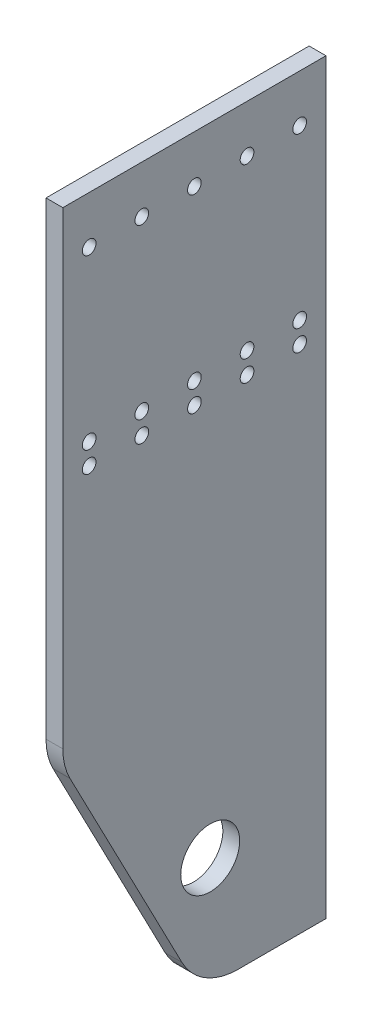
SolidWorks part; units mm, degrees
material "Q355"
ref_plane "前视基准面" through (0, 0, 0) normal (0, 0, 1) x (1, 0, 0)
ref_plane "上视基准面" through (0, 0, 0) normal (0, 1, 0) x (1, 0, 0)
ref_plane "右视基准面" through (0, 0, 0) normal (1, 0, 0) x (0, 0, -1)
sketch "草图1" plane through (0, 0, 0) normal (1, 0, 0) x (0, 0, -1)
  line L1 (0, 0) -> (250, 0)
  line L2 (0, 0) -> (0, 750)
  line L3 (0, 750) -> (250, 750)
  line L4 (250, 0) -> (250, 750)
  dimension "D1" = 250
  dimension "D2" = 750
extrude "凸台-拉伸1" add sketch "草图1" along normal blind 16 contours L2 L3 L4 L1
sketch "草图3" plane through (0, 0, 0) normal (-1, 0, 0) x (0, 0, 1)
  line L6 (-130, 0) -> (0, 250)
  line L7 (0, 0) -> (-250, 0) construction
  line L8 (0, 0) -> (0, 750) construction
  line L9 (0, 250) -> (0, 0)
  line L10 (0, 0) -> (-130, 0)
  line L11 (-250, 0) -> (-250, 750) construction
  dimension "D1" = 120
  dimension "D2" = 250
extrude "切除-拉伸2" cut sketch "草图3" against normal blind 20
sketch "草图5" plane through (0, 0, 0) normal (-1, 0, 0) x (0, 0, 1)
  line L0 (-250, 0) -> (-250, 750) construction
  line L1 (0, 750) -> (-250, 750) construction
  circle A0 centre (-225, 665) radius 6.5
  circle A1 centre (-225, 505) radius 6.5
  circle A2 centre (-225, 485) radius 6.5
  dimension "D1" = 25
  dimension "D3" = 13
  dimension "D5" = 20
  dimension "D2" = 85
  dimension "D4" = 160
extrude "切除-拉伸3" cut sketch "草图5" against normal through all
pattern_linear "阵列(线性)1" count 5 spacing 50 along (0, 0, 1) of "切除-拉伸3"
sketch "草图6" plane through (0, 0, 0) normal (-1, 0, 0) x (0, 0, 1)
  line L0 (0, 750) -> (-250, 750) construction
  line L2 (-250, 0) -> (-250, 750) construction
  circle A0 centre (-140, 105) radius 28
  dimension "D1" = 56
  dimension "D3" = 645
  dimension "D2" = 110
extrude "切除-拉伸4" cut sketch "草图6" against normal through all
fillet "圆角1" radius 60 2 edges at (8, 0, -130) (8, 250, 0)
sketch "草图7" plane through (16, 0, 0) normal (1, 0, 0) x (0, 0, -1)
  line L0 (250, 0) -> (250, 750) construction
  line L1 (0, 750) -> (250, 750)
  line L2 (0, 750) -> (0, 710)
  line L3 (0, 710) -> (250, 710)
  line L4 (250, 750) -> (250, 710)
  dimension "D1" = 40
extrude "切除-拉伸5" cut sketch "草图7" against normal blind 66
